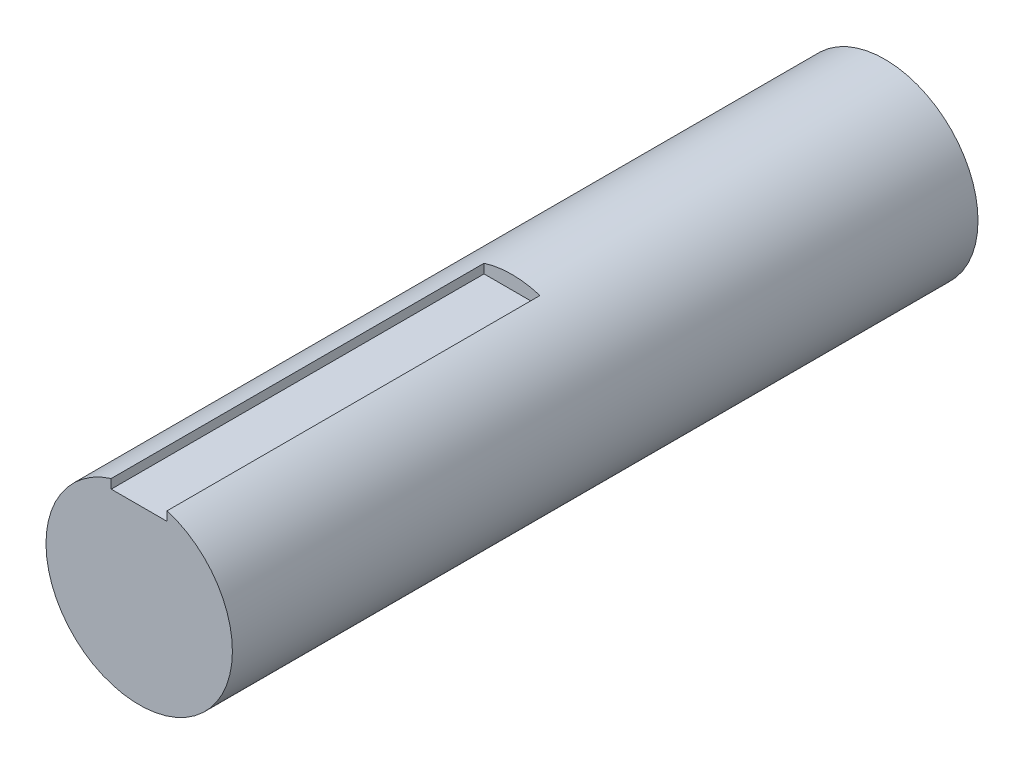
SolidWorks part; units mm, degrees
ref_plane "前视基准面" through (0, 0, 0) normal (0, 0, 1) x (1, 0, 0)
ref_plane "上视基准面" through (0, 0, 0) normal (0, 1, 0) x (1, 0, 0)
ref_plane "右视基准面" through (0, 0, 0) normal (1, 0, 0) x (0, 0, -1)
sketch "草图1" plane through (0, 0, 0) normal (0, 0, 1) x (1, 0, 0)
  circle A0 centre (0, 0) radius 2.5
  dimension "D1" = 5
extrude "拉伸1" add sketch "草图1" along normal blind 20
sketch "草图2" plane through (0, 0, 20) normal (0, 0, 1) x (1, 0, 0)
  line L0 (0, 3.1394) -> (0, -1.4909) construction
  line L1 (-0.75, 2.805) -> (0.75, 2.805)
  line L2 (-0.75, 2.805) -> (-0.75, 2.137)
  line L3 (-0.75, 2.137) -> (0.75, 2.137)
  line L4 (0.75, 2.805) -> (0.75, 2.137)
  dimension "D1" = 1.5
extrude "切除-拉伸1" cut sketch "草图2" against normal blind 10
